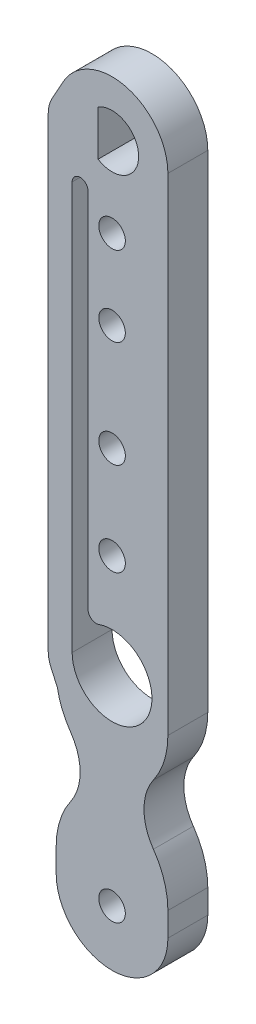
SolidWorks part; units mm, degrees
ref_plane "前视基准面" through (0, 0, 0) normal (0, 0, 1) x (1, 0, 0)
ref_plane "上视基准面" through (0, 0, 0) normal (0, 1, 0) x (1, 0, 0)
ref_plane "右视基准面" through (0, 0, 0) normal (1, 0, 0) x (0, 0, -1)
sketch "草图1" plane through (0, 0, 0) normal (0, 0, 1) x (1, 0, 0)
  line L0 (-340.183, 59.2118) -> (-340.183, 86.4608)
  line L1 (-341.383, 86.4608) -> (-341.383, 55.8177)
  line L2 (-334.183, 54.0177) -> (-334.183, 90.6177)
  line L3 (-334.183, 40.8177) -> (-334.183, 42.6177)
  line L4 (-342.583, 42.6177) -> (-342.583, 40.8177)
  line L5 (-342.9649, 54.0204) -> (-342.4954, 52.9959)
  line L6 (-343.183, 89.9978) -> (-343.183, 55.0202)
  line L7 (-342.0884, 92.5953) -> (-342.8828, 91.1601)
  line L8 (-339.433, 90.6177) -> (-339.433, 88.9155)
  line L9 (-339.433, 90.6177) -> (-339.433, 92.3199)
  arc A0 (-340.183, 86.4608) -> (-341.383, 86.4608) centre (-340.783, 86.4608) ccw
  arc A1 (-341.383, 55.8177) -> (-339.383, 58.6462) centre (-338.383, 55.8177) ccw
  arc A2 (-340.183, 59.2118) -> (-339.383, 58.6462) centre (-339.583, 59.2118) ccw
  arc A3 (-339.433, 88.9155) -> (-339.433, 92.3199) centre (-338.383, 90.6177) ccw
  circle A4 centre (-338.383, 84.6177) radius 1
  arc A5 (-335.2712, 50.5719) -> (-334.183, 54.0177) centre (-340.183, 54.0177) ccw
  arc A6 (-335.2712, 50.5719) -> (-335.2712, 46.0636) centre (-332.058, 48.3177) ccw
  arc A7 (-334.183, 42.6177) -> (-335.2712, 46.0636) centre (-340.183, 42.6177) ccw
  arc A8 (-342.583, 40.8177) -> (-334.183, 40.8177) centre (-338.383, 40.8177) ccw
  arc A9 (-341.4949, 46.0636) -> (-342.583, 42.6177) centre (-336.583, 42.6177) ccw
  arc A10 (-341.4949, 46.0636) -> (-341.4949, 50.5719) centre (-344.708, 48.3177) ccw
  arc A11 (-342.4954, 52.9959) -> (-341.4949, 50.5719) centre (-336.583, 54.0177) ccw
  arc A12 (-343.183, 55.0202) -> (-342.9649, 54.0204) centre (-340.783, 55.0202) ccw
  arc A13 (-342.8828, 91.1601) -> (-343.183, 89.9978) centre (-340.783, 89.9978) ccw
  arc A14 (-334.183, 90.6177) -> (-342.0884, 92.5953) centre (-338.383, 90.6177) ccw
  circle A15 centre (-338.383, 78.6177) radius 1
  circle A21 centre (-338.383, 40.8177) radius 1
  circle A32 centre (-338.383, 63.6177) radius 1
  circle A33 centre (-338.383, 70.6177) radius 1
  dimension "D1" = 2
  dimension "D3" = 3
  dimension "D4" = 2
  dimension "D5" = 2
  dimension "D2" = 49.8
  dimension "D6" = 6
  dimension "D7" = 6
extrude "凸台-拉伸1" add sketch "草图1" along normal blind 3
